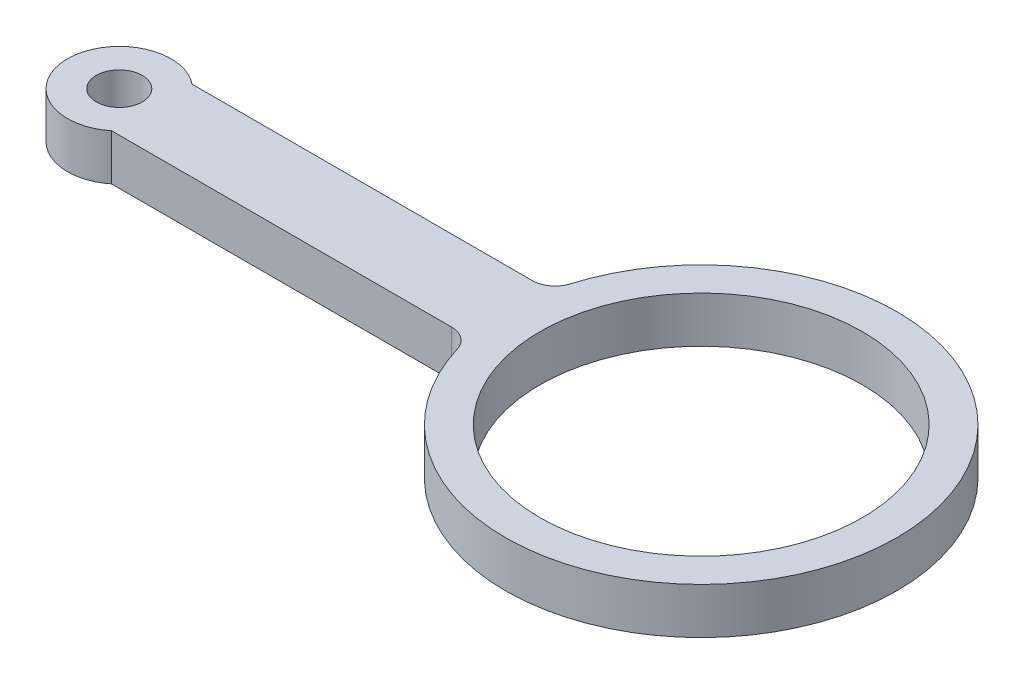
SolidWorks part; units mm, degrees
ref_plane "Front Plane" through (0, 0, 0) normal (0, 0, 1) x (1, 0, 0)
ref_plane "Top Plane" through (0, 0, 0) normal (0, 1, 0) x (1, 0, 0)
ref_plane "Right Plane" through (0, 0, 0) normal (1, 0, 0) x (0, 0, -1)
sketch "Sketch1" plane through (0, 0, 0) normal (0, 1, 0) x (1, 0, 0)
  line L0 (-6.4102, -0.5658) -> (8.3556, -0.5658)
  line L1 (-6.4102, -4.0658) -> (8.3556, -4.0658)
  arc A0 (-6.4102, -0.5658) -> (-6.4102, -4.0658) centre (-7.8244, -2.3158) ccw
  arc A1 (9.2884, -4.7055) -> (9.2884, 0.0739) centre (17.4456, -2.3158) ccw
  circle A2 centre (17.4456, -2.3158) radius 7
  circle A3 centre (-7.8244, -2.3158) radius 1
  arc A4 (9.2884, -4.7055) -> (8.3556, -4.0658) centre (8.3556, -5.0658) ccw
  arc A5 (8.3556, -0.5658) -> (9.2884, 0.0739) centre (8.3556, 0.4342) ccw
  dimension "D1" = 4.5
  dimension "D2" = 17
  dimension "D3" = 14
  dimension "D4" = 2
  dimension "D11" = 2
  dimension "D12" = 2
  dimension "D5" = 25.27
  dimension "D6" = 3.5
  dimension "D7" = 9.09
  dimension "D8" = 5.5
  dimension "D9" = 2.75
  dimension "D10" = 1.75
  dimension "D13" = 7.8244
  dimension "D14" = 2.3158
extrude "Boss-Extrude1" add sketch "Sketch1" along normal blind 2
